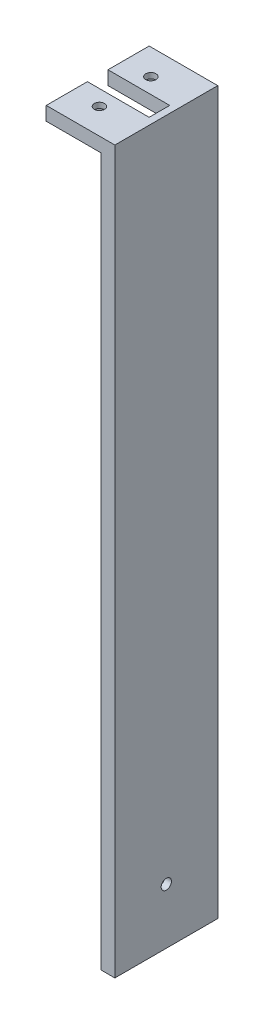
SolidWorks part; units mm, degrees
ref_plane "Plan de face" through (0, 0, 0) normal (0, 0, 1) x (1, 0, 0)
ref_plane "Plan de dessus" through (0, 0, 0) normal (0, 1, 0) x (1, 0, 0)
ref_plane "Plan de droite" through (0, 0, 0) normal (1, 0, 0) x (0, 0, -1)
sketch "Esquisse1" plane through (0, 0, 0) normal (0, 0, 1) x (1, 0, 0)
  line L0 (90.805, 44.0887) -> (116.205, 44.0887)
  line L1 (-116.205, 44.0887) -> (116.205, 44.0887) construction
  line L2 (116.205, 44.0887) -> (116.205, -223.0115)
  line L3 (106.045, -194.8492) -> (106.045, -251.1737) construction
  point P8 (106.045, -223.0115)
  dimension "D1" = 25.4
extrude "Extru.-Mince1" add sketch "Esquisse1" against normal up to surface (38.1 mm away) thin
sketch "Esquisse2" plane through (116.205, 0, 0) normal (1, 0, 0) x (0, 0, -1)
  circle A0 centre (19.05, -202.4692) radius 1.8986
  circle A1 centre (19.05, -202.4692) radius 1.8986 construction
extrude "Enlèv. mat.-Extru.1" cut sketch "Esquisse2" against normal through all
sketch "Esquisse3" plane through (0, 39.0087, 0) normal (0, -1, 0) x (1, 0, 0)
  line L0 (100.965, -28.575) -> (100.965, -9.525) construction
  line L1 (100.965, -23.7357) -> (96.774, -26.1553)
  line L2 (96.774, -26.1553) -> (96.774, -30.9947)
  line L3 (96.774, -30.9947) -> (100.965, -33.4143)
  line L4 (100.965, -33.4143) -> (105.156, -30.9947)
  line L5 (105.156, -30.9947) -> (105.156, -26.1553)
  line L6 (105.156, -26.1553) -> (100.965, -23.7357)
  line L7 (100.965, -4.6857) -> (96.774, -7.1053)
  line L8 (96.774, -7.1053) -> (96.774, -11.9447)
  line L9 (96.774, -11.9447) -> (100.965, -14.3643)
  line L10 (100.965, -14.3643) -> (105.156, -11.9447)
  line L11 (105.156, -11.9447) -> (105.156, -7.1053)
  line L12 (105.156, -7.1053) -> (100.965, -4.6857)
  line L13 (111.125, -38.1) -> (111.125, 0) construction
  line L14 (90.805, -38.1) -> (111.125, -38.1) construction
  line L15 (116.205, -38.1) -> (116.205, 0) construction
  circle A0 centre (100.965, -28.575) radius 4.191 construction
  circle A1 centre (100.965, -9.525) radius 4.191 construction
  point P18 (111.125, -19.05)
  point P19 (100.965, -19.05)
  point P22 (100.965, -38.1)
  dimension "D1" = 8.382
  dimension "D2" = 19.05
extrude "Enlèv. mat.-Extru.2" cut sketch "Esquisse3" against normal blind 3.048
hole_wizard "Dégagement #61" positions "Esquisse4" profile "Esquisse5" hole size "#6" standard "Ansi Inch" end condition through all
sketch "Esquisse4" plane through (0, 42.0567, 0) normal (0, -1, 0) x (-1, 0, 0)
  line L0 (-100.965, 38.1) -> (-100.965, 0) construction
  line L1 (-96.774, 7.1053) -> (-96.774, 11.9447) construction
  line L2 (-96.774, 26.1553) -> (-96.774, 30.9947) construction
  point P0 (-100.965, 28.575)
  point P4 (-100.965, 9.525)
  point P9 (-96.774, 9.525)
  point P13 (-96.774, 28.575)
sketch "Esquisse5" plane through (100.965, 42.0567, -28.575) normal (1, 0, 0) x (0, 0, -1)
  line L0 (0, 0) -> (0, 2.032)
  line L1 (0, 2.032) -> (1.8986, 2.032)
  line L2 (1.8986, 2.032) -> (1.8986, 0)
  line L5 (1.8986, 0) -> (0, 0)
  line L11 (0, -6.35) -> (0, 107.95) construction
  dimension "Diamètre du perçage jusqu'au prochain" = 3.7973
  dimension "Profondeur du perçage jusqu'au prochain" = 2.032
sketch "Esquisse6" plane through (90.805, 0, 0) normal (-1, 0, 0) x (0, 0, 1)
  line L0 (-38.1, 44.0887) -> (0, 44.0887) construction
  line L1 (-22.86, 44.0887) -> (-15.24, 44.0887)
  line L2 (-22.86, 44.0887) -> (-22.86, -223.0115)
  line L3 (-22.86, -223.0115) -> (-15.24, -223.0115)
  line L4 (-15.24, 44.0887) -> (-15.24, -223.0115)
  line L7 (-38.1, -223.0115) -> (0, -223.0115) construction
  point P7 (0, 0)
  point P8 (-14.3517, -220.1622)
  dimension "D1" = 7.62
extrude "Enlèv. mat.-Extru.3" cut sketch "Esquisse6" against normal blind 22.86
